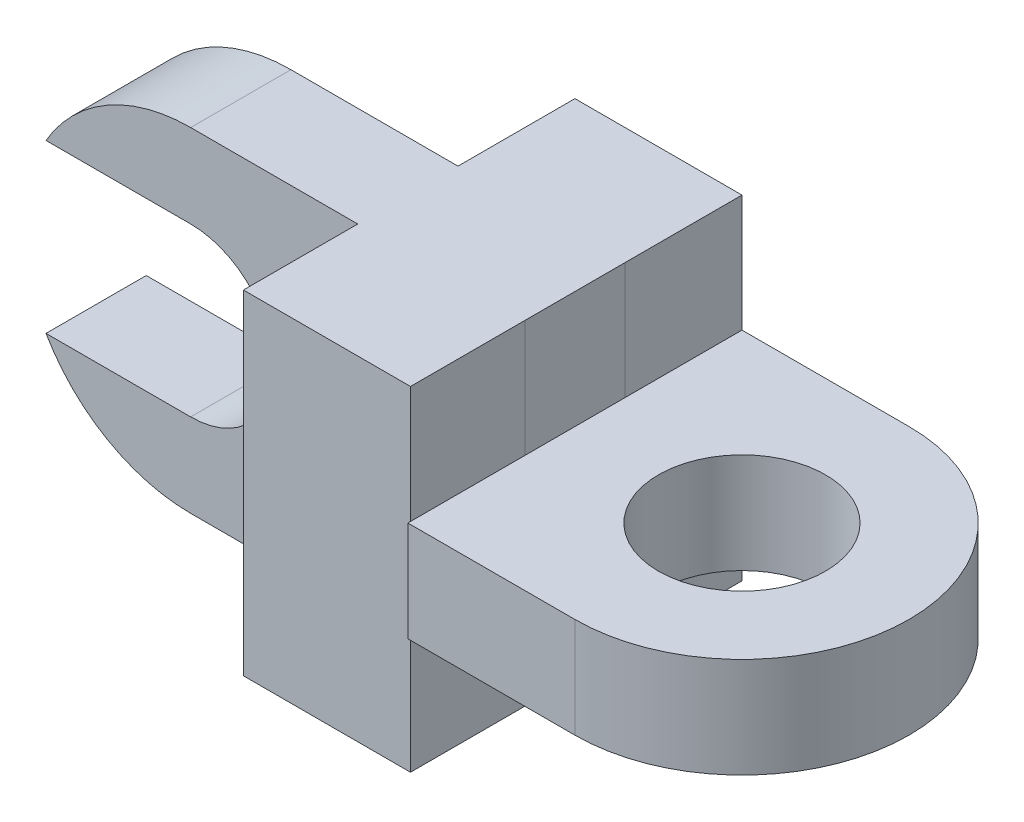
SolidWorks part; units mm, degrees
ref_plane "Front Plane" through (0, 0, 0) normal (0, 0, 1) x (1, 0, 0)
ref_plane "Top Plane" through (0, 0, 0) normal (0, 1, 0) x (1, 0, 0)
ref_plane "Right Plane" through (0, 0, 0) normal (1, 0, 0) x (0, 0, -1)
sketch "Sketch1" plane through (0, 0, 0) normal (0, 0, 1) x (1, 0, 0)
  line L0 (-100, 25) -> (-143.3013, 25)
  line L1 (-100, 50) -> (0, 50)
  line L3 (-100, -50) -> (0, -50)
  line L4 (100, 15) -> (100, -15)
  line L5 (-100, -25) -> (-143.3013, -25)
  line L6 (0, 50) -> (0, 15)
  line L8 (0, -15) -> (100, -15)
  line L9 (0, 15) -> (100, 15)
  line L10 (0, -15) -> (0, -50)
  line L11 (100, 50) -> (100, -50) construction
  line L13 (0, 50) -> (0, -50) construction
  arc A0 (-143.3013, -25) -> (-100, -50) centre (-100, 0) ccw
  arc A1 (-100, -25) -> (-100, 25) centre (-100, 0) ccw
  arc A2 (-100, 50) -> (-143.3013, 25) centre (-100, 0) ccw
  point P0 (0, 0)
  dimension "D3" = 50
  dimension "D1" = 50
  dimension "D2" = 100
  dimension "D5" = 15
  dimension "D6" = 15
  dimension "D4" = 100
extrude "Boss-Extrude1" add sketch "Sketch1" against normal blind 30
sketch "Sketch2" plane through (0, 15, 0) normal (0, 1, 0) x (1, 0, 0)
  line L0 (49.9987, 65) -> (-0.0013, 65)
  line L1 (-0.0013, 65) -> (-0.0013, -35)
  line L4 (-0.0013, -35) -> (49.9987, -35)
  line L5 (100, 30) -> (100, 0) construction
  line L6 (100, 0) -> (0, 0) construction
  arc A0 (49.9987, -35) -> (49.9987, 65) centre (49.9987, 15) ccw
  dimension "D3" = 100
  dimension "D1" = 50.0013
  dimension "D2" = 15
  dimension "D4" = 30
extrude "Boss-Extrude2" add sketch "Sketch2" against normal blind 30 contours A0 L0 L1 L4
sketch "Sketch3" plane through (0, 15, 0) normal (0, 1, 0) x (1, 0, 0)
  line L0 (97.6957, 30) -> (100, 30)
  line L1 (100, 30) -> (100, 0)
  line L2 (100, 0) -> (97.6957, 0)
  arc A0 (97.6957, 0) -> (97.6957, 30) centre (49.9987, 15) ccw
extrude "Cut-Extrude1" cut sketch "Sketch3" against normal blind 64
sketch "Sketch4" plane through (0, 15, 0) normal (0, 1, 0) x (1, 0, 0)
  circle A0 centre (49.9987, 15) radius 25
  dimension "D1" = 50
extrude "Cut-Extrude2" cut sketch "Sketch4" against normal blind 93
sketch "Sketch6" plane through (0, 50, 0) normal (0, 1, 0) x (1, 0, 0)
  line L1 (-50.0013, -34.2134) -> (-0.0013, -34.2134)
  line L2 (-50.0013, -34.2134) -> (-50.0013, 65)
  line L3 (-50.0013, 65) -> (-0.0013, 65)
  line L4 (-0.0013, -34.2134) -> (-0.0013, 65)
  point P0 (-25.0013, 15.3933)
  dimension "D1" = 50
extrude "Boss-Extrude3" add sketch "Sketch6" against normal blind 100
